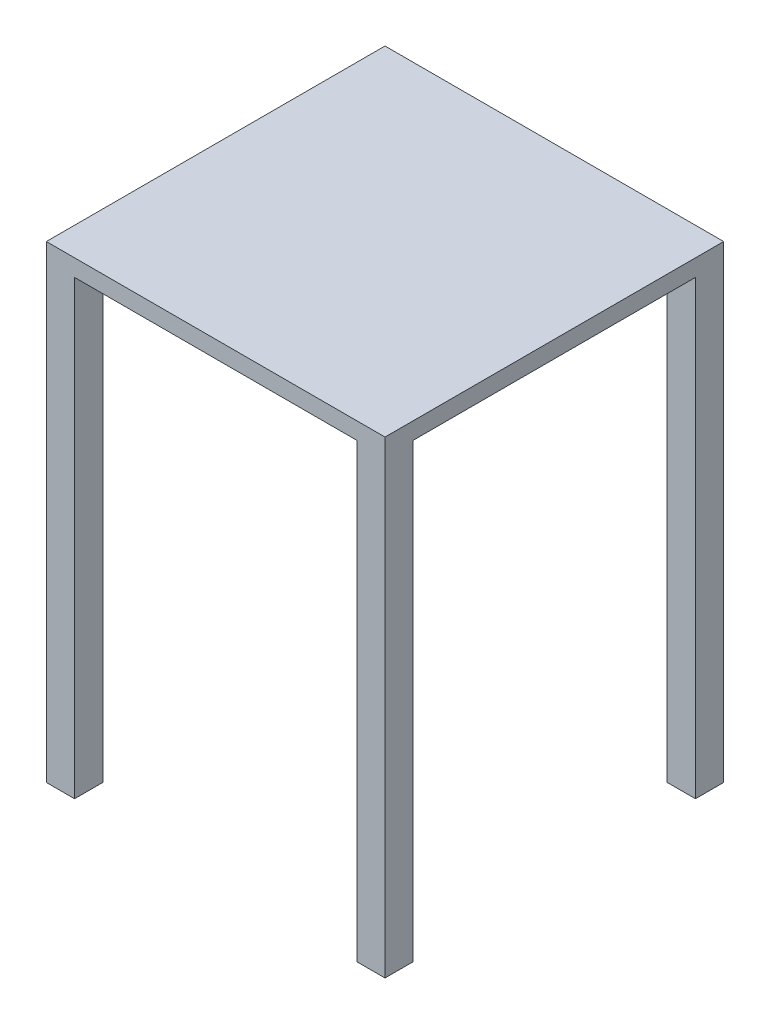
SolidWorks part; units mm, degrees
ref_plane "前视基准面" through (0, 0, 0) normal (0, 0, 1) x (1, 0, 0)
ref_plane "上视基准面" through (0, 0, 0) normal (0, 1, 0) x (1, 0, 0)
ref_plane "右视基准面" through (0, 0, 0) normal (1, 0, 0) x (0, 0, -1)
other "Configuration Table"
sketch "草图1" plane through (0, 0, 0) normal (0, 1, 0) x (1, 0, 0)
  line L1 (300, -300) -> (-300, -300)
  line L2 (300, -300) -> (300, 300)
  line L3 (300, 300) -> (-300, 300)
  line L4 (-300, -300) -> (-300, 300)
  line L5 (300, -300) -> (-300, 300) construction
  line L6 (300, 300) -> (-300, -300) construction
  point P0 (0, 0)
  dimension "D1" = 600
  dimension "D2" = 600
extrude "凸台-拉伸1" add sketch "草图1" along normal blind 30
sketch "草图2" plane through (0, 0, 0) normal (0, -1, 0) x (1, 0, 0)
  line L0 (-300, 300) -> (300, 300) construction
  line L1 (-300, 300) -> (-250, 300)
  line L2 (-300, 300) -> (-300, 250)
  line L3 (-300, 250) -> (-250, 250)
  line L4 (-250, 300) -> (-250, 250)
  line L5 (-300, -300) -> (-300, 300) construction
  line L6 (0, 0) -> (0, 300) construction
  line L7 (0, 0) -> (-300, 0) construction
  line L8 (250, 300) -> (250, 250)
  line L9 (300, 250) -> (250, 250)
  line L10 (300, 300) -> (300, 250)
  line L11 (300, 300) -> (250, 300)
  line L12 (300, -300) -> (250, -300)
  line L13 (300, -300) -> (300, -250)
  line L14 (300, -250) -> (250, -250)
  line L15 (250, -300) -> (250, -250)
  line L16 (-250, -300) -> (-250, -250)
  line L17 (-300, -250) -> (-250, -250)
  line L18 (-300, -300) -> (-300, -250)
  line L19 (-300, -300) -> (-250, -300)
  dimension "D1" = 50
  dimension "D2" = 50
extrude "凸台-拉伸2" add sketch "草图2" along normal blind 800
